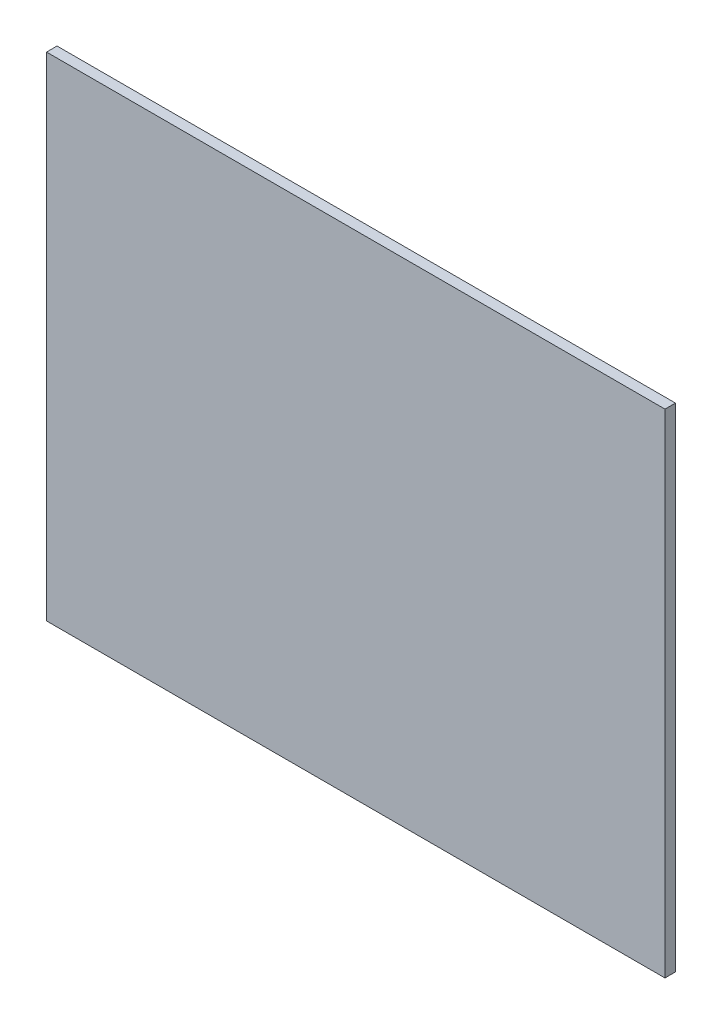
SolidWorks part; units mm, degrees
ref_plane "Front Plane" through (0, 0, 0) normal (0, 0, 1) x (1, 0, 0)
ref_plane "Top Plane" through (0, 0, 0) normal (0, 1, 0) x (1, 0, 0)
ref_plane "Right Plane" through (0, 0, 0) normal (1, 0, 0) x (0, 0, -1)
sketch "Esquisse1" plane through (0, 0, 0) normal (0, 0, 1) x (1, 0, 0)
  line L1 (0, 0) -> (-295, 0)
  line L2 (0, 0) -> (0, -235)
  line L3 (0, -235) -> (-295, -235)
  line L4 (-295, 0) -> (-295, -235)
  line L5 (-147.5, -235) -> (-147.5, 0) construction
  line L6 (0, -117.5) -> (-295, -117.5) construction
  point P100 (-147.5, -117.5)
  dimension "D1" = 295
  dimension "D2" = 235
extrude "Boss.-Extru.1" add sketch "Esquisse1" along normal blind 5
